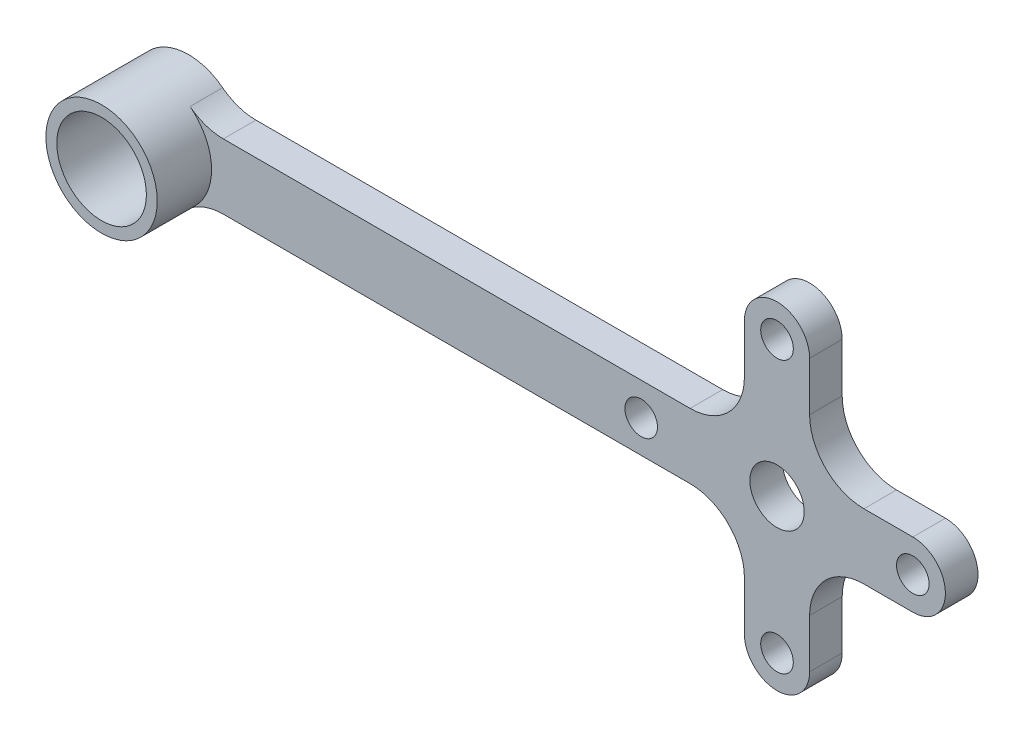
SolidWorks part; units mm, degrees
ref_plane "Plano frontal" through (0, 0, 0) normal (0, 0, 1) x (1, 0, 0)
ref_plane "Plano superior" through (0, 0, 0) normal (0, 1, 0) x (1, 0, 0)
ref_plane "Plano direito" through (0, 0, 0) normal (1, 0, 0) x (0, 0, -1)
sketch "Esboço1" plane through (0, 0, 0) normal (0, 0, 1) x (1, 0, 0)
  line L0 (0, 12.5) -> (0, -12.5) construction
  line L1 (3, 12.5) -> (3, 3)
  line L2 (-3, 12.5) -> (-3, 3)
  line L15 (-12.5, 0) -> (12.5, 0) construction
  line L18 (0, 0) -> (-57.17, 0) construction
  line L24 (0, 0) -> (-57.17, 0) construction
  line L25 (-3, -3) -> (-57.17, -3)
  line L26 (-3, 3) -> (-57.17, 3)
  line L27 (-12.5, 3) -> (-3, 3)
  line L28 (-12.5, -3) -> (-3, -3)
  line L29 (-3, -3) -> (-3, -12.5)
  line L30 (3, -3) -> (12.5, -3)
  line L31 (3, 3) -> (12.5, 3)
  line L32 (3, -3) -> (3, -12.5)
  circle A14 centre (0, 0) radius 2.5
  circle A15 centre (-12.5, 0) radius 1.5
  circle A19 centre (0, 0) radius 12.5 construction
  arc A27 (-57.17, 3) -> (-57.17, -3) centre (-57.17, 0) ccw
  circle A28 centre (0, 12.5) radius 1.5
  circle A29 centre (12.5, 0) radius 1.5
  circle A30 centre (0, -12.5) radius 1.5
  arc A31 (3, 12.5) -> (-3, 12.5) centre (0, 12.5) ccw
  arc A32 (-3, -12.5) -> (3, -12.5) centre (0, -12.5) ccw
  arc A34 (12.5, -3) -> (12.5, 3) centre (12.5, 0) ccw
  point P0 (0, 0)
  point P11 (0, 0)
  point P12 (-28.585, 0)
  point P16 (0, 0)
  point P21 (-28.585, 0)
  point P22 (0, 0)
  point P26 (0, 0)
  dimension "D1" = 4
  dimension "D3" = 3
  dimension "D2" = 25
  dimension "D4" = 5
  dimension "D5" = 57.17
  dimension "D6" = 3
  dimension "D7" = 3
  dimension "D8" = 3
extrude "Ressalto-extrusão3" add sketch "Esboço1" along normal mid plane 3 contours L30 A34 L31 L1 A31 L2 L26 A27 L25 L29 A32 L32 A14 A15 A28 A29 A30
sketch "Esboço2" plane through (0, 0, 1.5) normal (0, 0, 1) x (1, 0, 0)
  circle A2 centre (-57.17, 0) radius 5.125
  dimension "D1" = 10.25
extrude "Ressalto-extrusão4" add sketch "Esboço2" along normal blind 5 and the other way up to surface other way up to face at (2.5, 0, -1.5)
sketch "Esboço3" plane through (0, 0, 6.5) normal (0, 0, 1) x (1, 0, 0)
  circle A0 centre (-57.17, 0) radius 4.125
  circle A1 centre (-57.17, 0) radius 5.125 construction
  point P3 (0, 0)
  point P4 (0, 0)
  dimension "D1" = 8.25
extrude "Corte-extrusão1" cut sketch "Esboço3" against normal blind 10
fillet "Filete1" radius 5 6 edges at (3, -3, 0) (-3, -3, 0) (-3, 3, 0) (3, 3, 0) (-53.0148, 3, 0) (-53.0148, -3, 0)
move or copy body "Corpo-Converter em corpo de malha1" [suppressed] bodies to move or copy 106 copy no translate (0, 0, 0) parameters "D1"=0, "D2"=0, "D3"=0
